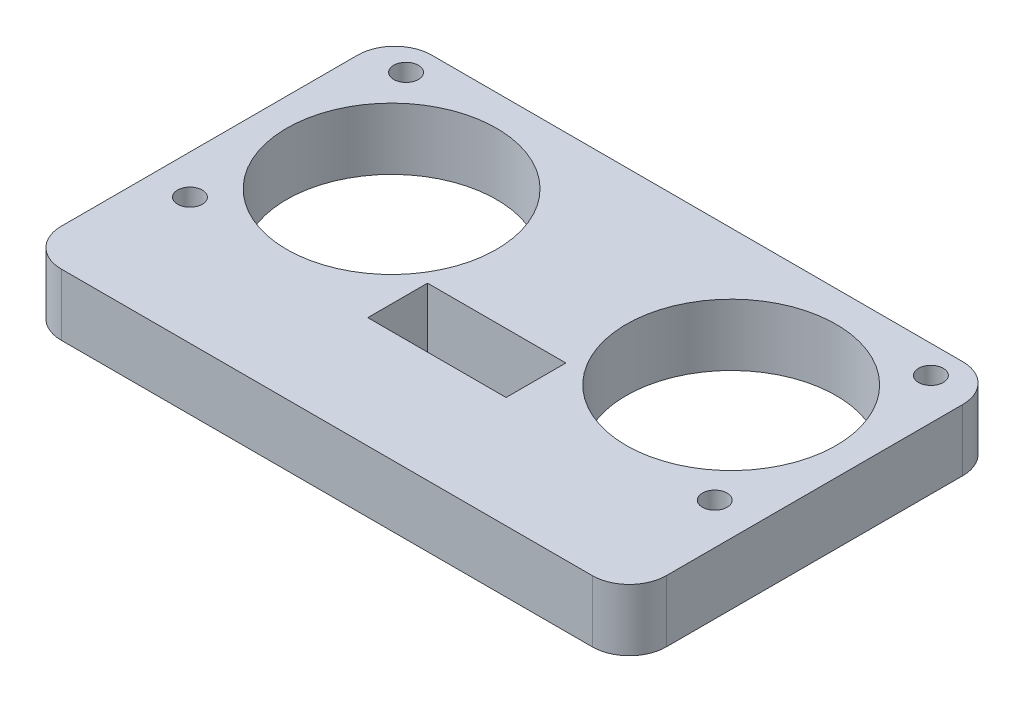
SolidWorks part; units mm, degrees
ref_plane "Front Plane" through (0, 0, 0) normal (0, 0, 1) x (1, 0, 0)
ref_plane "Top Plane" through (0, 0, 0) normal (0, 1, 0) x (1, 0, 0)
ref_plane "Right Plane" through (0, 0, 0) normal (1, 0, 0) x (0, 0, -1)
sketch "Sketch1" plane through (0, 0, 0) normal (0, 1, 0) x (1, 0, 0)
  circle A0 centre (0, 0) radius 20
  circle A1 centre (0, 0) radius 21
  dimension "D1" = 40
  dimension "D2" = 42
extrude "Boss-Extrude1" add sketch "Sketch1" along normal blind 3.5 contours A1 | A0
ref_plane "Plane1" through (0, 3.5, 0) normal (0, 1, 0) x (1, 0, 0)
sketch "Sketch2" plane through (0, 3.5, 0) normal (0, 1, 0) x (1, 0, 0)
  line L0 (-23.55, 0) -> (23.55, 0) construction
  line L1 (-29, -29) -> (29, -29)
  line L2 (-29, -29) -> (-29, 29)
  line L3 (-29, 29) -> (29, 29)
  line L4 (29, -29) -> (29, 29)
  line L5 (-29, -29) -> (29, 29) construction
  line L6 (-29, 29) -> (29, -29) construction
  line L7 (-28.2, -28.2) -> (28.2, -28.2) construction
  line L8 (-28.2, -28.2) -> (-28.2, 28.2) construction
  line L9 (-28.2, 28.2) -> (28.2, 28.2) construction
  line L10 (28.2, -28.2) -> (28.2, 28.2) construction
  line L11 (-28.2, -28.2) -> (28.2, 28.2) construction
  line L12 (-28.2, 28.2) -> (28.2, -28.2) construction
  line L13 (-23.55, 28.2) -> (-23.55, 23.55) construction
  line L14 (-23.55, 23.55) -> (-28.2, 23.55) construction
  line L15 (0, 28.2) -> (0, -28.2) construction
  line L16 (0, 29) -> (0, 49) construction
  line L17 (-22.5, 49) -> (22.5, 49) construction
  line L18 (-22.5, 49) -> (-22.5, 29) construction
  line L19 (22.5, 49) -> (22.5, 29) construction
  line L20 (0, 49) -> (0, 48) construction
  line L21 (-4.9, 48) -> (4.9, 48) construction
  line L22 (-4.9, 48) -> (-4.9, 44.56) construction
  line L23 (-4.9, 44.56) -> (4.9, 44.56) construction
  line L24 (4.9, 44.56) -> (4.9, 48) construction
  line L25 (-24.5, 29) -> (-24.5, 51)
  line L26 (-24.5, 51) -> (24.5, 51)
  line L27 (24.5, 51) -> (24.5, 29)
  line L28 (-13.76, 39) -> (13.76, 39) construction
  line L29 (-5.6, 48.7) -> (5.6, 48.7)
  line L31 (5.6, 43.86) -> (-5.6, 43.86)
  line L32 (-5.6, 43.86) -> (-5.6, 48.7)
  line L33 (5.6, 43.86) -> (5.6, 48.7)
  line L34 (-24.5, 51) -> (-24.5, 59)
  line L35 (-24.5, 59) -> (24.5, 59)
  line L36 (24.5, 59) -> (24.5, 51)
  line L37 (0, 0) -> (34, 0) construction
  line L38 (29, 5) -> (39, 5)
  line L39 (29, -5) -> (39, -5)
  line L40 (39, 5) -> (39, -5)
  line L41 (-29, -5) -> (-39, -5)
  line L42 (-39, 5) -> (-39, -5)
  line L43 (-29, 5) -> (-39, 5)
  circle A0 centre (-23.55, 23.55) radius 2.55 construction
  circle A1 centre (23.55, 23.55) radius 2.55 construction
  circle A2 centre (23.55, -23.55) radius 2.55 construction
  circle A3 centre (-23.55, -23.55) radius 2.55 construction
  circle A4 centre (0, 0) radius 5.5563 construction
  circle A5 centre (13.76, 39) radius 7.5 construction
  circle A6 centre (-13.76, 39) radius 7.5 construction
  circle A7 centre (-13.76, 39) radius 8.5
  circle A8 centre (13.76, 39) radius 8.5
  circle A9 centre (0, 0) radius 6.55
  circle A10 centre (-23.55, 23.55) radius 3.55
  circle A11 centre (23.55, 23.55) radius 3.55
  circle A12 centre (23.55, -23.55) radius 3.55
  circle A13 centre (-23.55, -23.55) radius 3.55
  circle A14 centre (34, 0) radius 2.55
  circle A15 centre (-34, 0) radius 2.55
  point P0 (0, 0)
  point P5 (0, 0)
  point P15 (0, 0)
  point P34 (0, 49)
  point P40 (0, 48)
  point P49 (0, 39)
  point P56 (0, 43.86)
  point P59 (0, 48.7)
  point P70 (34, 0)
  dimension "D4" = 5.1
  dimension "D5" = 11.1125
  dimension "D15" = 15
  dimension "D16" = 17
  dimension "D17" = 0.7
  dimension "D20" = 13.1
  dimension "D21" = 7.1
  dimension "D22" = 8
  dimension "D24" = 5.1
  dimension "D25" = 5
  dimension "D1" = 58
  dimension "D2" = 56.4
  dimension "D3" = 47.1
  dimension "D6" = 20
  dimension "D7" = 45
  dimension "D8" = 1
  dimension "D9" = 9.8
  dimension "D10" = 3.44
  dimension "D11" = 2
  dimension "D12" = 2
  dimension "D13" = 2
  dimension "D14" = 27.52
  dimension "D18" = 0.7
  dimension "D19" = 0.7
  dimension "D23" = 34
  dimension "D26" = 5
extrude "Boss-Extrude2" add sketch "Sketch2" along normal blind 5 contours L1 L4 L3 L2 A4 A1 A0 A2 A3 | L27 L26 L25 L3 A8 A7 L33 L31 L32 L29 | L40 L38 L4 L39 A14 | L2 L43 L42 L41 A15
sketch "Sketch3" plane through (0, 3.5, 0) normal (0, 1, 0) x (1, 0, 0)
  line L0 (-5.6, 48.7) -> (5.6, 48.7)
  line L1 (5.6, 48.7) -> (5.6, 43.86)
  line L2 (5.6, 43.86) -> (-5.6, 43.86)
  line L3 (-5.6, 43.86) -> (-5.6, 48.7)
  line L4 (-13.76, 47.5) -> (-13.76, 30.5) construction
  line L5 (13.76, 47.5) -> (13.76, 30.5) construction
  line L6 (-24.5, 29) -> (24.5, 29)
  line L7 (24.5, 29) -> (24.5, 51)
  line L8 (24.5, 51) -> (-24.5, 51)
  line L9 (-24.5, 51) -> (-24.5, 29)
  line L10 (-24.5, 51) -> (-24.5, 59)
  line L11 (-24.5, 59) -> (24.5, 59)
  line L12 (24.5, 59) -> (24.5, 51)
  circle A0 centre (-13.76, 39) radius 8.5 construction
  circle A1 centre (-13.76, 39) radius 8.5
  circle A2 centre (13.76, 39) radius 8.5 construction
  circle A3 centre (13.76, 39) radius 8.5
  dimension "D1" = 8
sketch "Sketch4" plane through (0, 3.5, 0) normal (0, 1, 0) x (1, 0, 0)
  line L4 (-5.6791, 42.84) -> (-5.6791, 38)
  line L5 (5.5209, 38) -> (5.5209, 42.84)
  line L10 (-24.5, 29) -> (-24.5, 37)
  line L11 (-24.5, 51) -> (-24.5, 29) construction
  line L12 (24.5, 29) -> (24.5, 37)
  line L13 (24.5, 29) -> (24.5, 51) construction
  line L14 (-24.5, 37) -> (-24.5, 59)
  line L15 (24.5, 37) -> (24.5, 59)
  line L16 (-24.5, 59) -> (24.5, 59)
  line L17 (-24.5, 37) -> (24.5, 37)
  line L18 (0, 59) -> (0, 37) construction
  line L23 (-5.6791, 38) -> (5.5209, 38)
  line L24 (5.5209, 42.84) -> (-5.6791, 42.84)
  line L25 (-5.6791, 58) -> (5.5209, 58) construction
  line L26 (5.5209, 58) -> (5.5209, 53.16) construction
  line L27 (5.5209, 53.16) -> (-5.6791, 53.16) construction
  line L28 (-5.6791, 53.16) -> (-5.6791, 58) construction
  line L29 (-13.75, 56.5) -> (-13.75, 39.5) construction
  line L30 (-13.75, 48) -> (13.75, 48) construction
  circle A4 centre (-13.75, 48) radius 8.5
  circle A5 centre (13.75, 48) radius 8.5
  point P53 (0, 48)
  dimension "D2" = 17
  dimension "D1" = 8
  dimension "D3" = 22
  dimension "D4" = 1
  dimension "D5" = 5.5209
  dimension "D6" = 11.2
  dimension "D7" = 4.84
  dimension "D8" = 27.5
extrude "Ignore" add sketch "Sketch3" along normal blind 5 contours L3 L2 L1 L0 | L12 L11 L10 L8 | A3 | A1
extrude "Cut-Extrude2" cut sketch "Sketch4" along normal through all contours A4 | A5 | L28 L27 L26 L25 | L5 L24 L4 L23
fillet "Fillet1" radius 3 10 edges at (29, 6, -29) (39, 6, 5) (39, 6, -5) (29, 6, 29) (-29, 6, 29) (-39, 6, 5) (-39, 6, -5) (-29, 6, -29) (24.5, 6, -59) (-24.5, 6, -59)
sketch "Sketch5" plane through (0, 0, 0) normal (0, 0, 1) x (1, 0, 0)
  line L0 (-21, 3.5) -> (21, 3.5)
  line L1 (21, 3.5) -> (21, 0)
  line L2 (21, 0) -> (-21, 0)
  line L3 (-21, 0) -> (-21, 3.5)
extrude "Cut-Extrude3" cut sketch "Sketch5" against normal mid plane 50
sketch "Sketch6" plane through (0, 8.5, 0) normal (0, 1, 0) x (1, 0, 0)
  line L0 (-26, 29) -> (24.5, 29)
  line L1 (24.5, 29) -> (43.3219, 29)
  line L2 (43.3219, 29) -> (43.3219, -33.143)
  line L5 (-38.2971, 29) -> (-26, 29)
  line L6 (43.3219, -33.143) -> (-52.0728, -33.143)
  line L7 (-52.0728, -33.143) -> (-52.0728, 29)
  line L8 (-52.0728, 29) -> (-38.2971, 29)
extrude "Cut-Extrude5" cut sketch "Sketch6" against normal blind 10
fillet "Fillet2" radius 3 2 edges at (24.5, 6, -29) (-24.5, 6, -29)
sketch "Sketch8" plane through (0, 3.5, 0) normal (0, -1, 0) x (1, 0, 0)
  line L0 (-22.25, -48) -> (22.25, -48) construction
  line L1 (-0.0791, -42.84) -> (-0.0791, -54.7233) construction
  line L2 (5.5209, -42.84) -> (-5.6791, -42.84) construction
  line L4 (-22.6, -58.1) -> (22.6, -58.1)
  line L5 (-22.6, -58.1) -> (-22.6, -37.9)
  line L6 (-22.6, -37.9) -> (22.6, -37.9)
  line L7 (22.6, -58.1) -> (22.6, -37.9)
  line L8 (-22.6, -58.1) -> (22.6, -37.9) construction
  line L9 (-22.6, -37.9) -> (22.6, -58.1) construction
  circle A0 centre (-13.75, -48) radius 8.5 construction
  circle A1 centre (13.75, -48) radius 8.5 construction
  circle A2 centre (21.1709, -39.25) radius 1
  circle A3 centre (21.1709, -56.75) radius 1
  circle A4 centre (-21.3291, -56.75) radius 1
  circle A5 centre (-21.3291, -39.25) radius 1
  point P18 (0, -48)
  point P23 (0, 0)
  dimension "D2" = 2
  dimension "D3" = 8.75
  dimension "D1" = 44.5
  dimension "D4" = 8.75
  dimension "D5" = 42.5
  dimension "D6" = 42.5
  dimension "D7" = 20.2
  dimension "D8" = 45.2
extrude "Cut-Extrude6" cut sketch "Sketch8" against normal blind 20 contours A5 | A4 | A3 | A2
